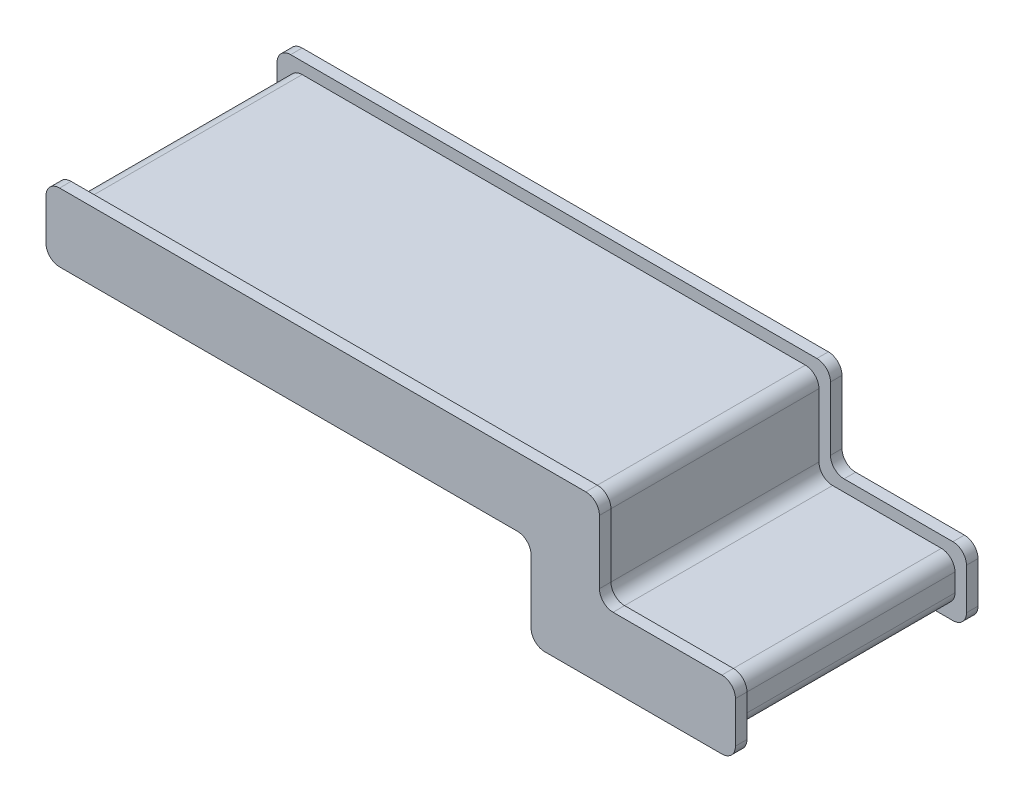
SolidWorks part; units mm, degrees
material "ABS"
ref_plane "X-Y Datum" through (0, 0, 0) normal (0, 0, 1) x (1, 0, 0)
ref_plane "X-Z Datum" through (0, 0, 0) normal (0, 1, 0) x (1, 0, 0)
ref_plane "Y-Z Datum" through (0, 0, 0) normal (1, 0, 0) x (0, 0, -1)
sketch "Sketch2" plane through (0, 0, 0) normal (0, 0, 1) x (1, 0, 0)
  line L6 (107, 10) -> (0, 10)
  line L7 (107, 10) -> (107, 0)
  line L8 (107, 0) -> (0, 0)
  line L9 (0, 10) -> (0, 0)
  dimension "D1" = 107
  dimension "D2" = 10
extrude "Boss-Extrude1" add sketch "Sketch2" along normal blind 48.42
sketch "Sketch3" plane through (0, 0, 48.42) normal (0, 0, 1) x (1, 0, 0)
  line L1 (107, 10) -> (117, 10)
  line L2 (107, 10) -> (107, -20)
  line L3 (107, -20) -> (117, -20)
  line L4 (117, 10) -> (117, -10)
  line L5 (117, -20) -> (147, -20)
  line L7 (117, -10) -> (147, -10)
  line L8 (147, -20) -> (147, -10)
  dimension "D1" = 10
  dimension "D2" = 30
  dimension "D3" = 10
  dimension "D4" = 30
extrude "Boss-Extrude2" add sketch "Sketch3" against normal up to surface (48.42 mm away) up to face at (53.5, 5, 0)
sketch "Sketch4" plane through (0, 0, 48.42) normal (0, 0, 1) x (1, 0, 0)
  line L0 (0, 10) -> (0, 0) construction
  line L1 (-2.54, 12.54) -> (119.54, 12.54)
  line L2 (-2.54, 12.54) -> (-2.54, -2.54)
  line L3 (-2.54, -2.54) -> (104.46, -2.54)
  line L12 (149.54, -22.54) -> (149.54, -7.46)
  line L13 (117, 10) -> (0, 10) construction
  line L14 (0, 0) -> (107, 0) construction
  line L15 (119.54, -7.46) -> (149.54, -7.46)
  line L16 (107, -20) -> (147, -20) construction
  line L17 (117, -10) -> (117, 10) construction
  line L18 (147, -10) -> (117, -10) construction
  line L19 (147, -20) -> (147, -10) construction
  line L20 (104.46, -22.54) -> (149.54, -22.54)
  line L21 (104.46, -2.54) -> (104.46, -22.54)
  line L22 (119.54, 12.54) -> (119.54, -7.46)
  line L23 (107, 0) -> (107, -20) construction
  point P18 (117, 0)
  dimension "D1" = 2.54
  dimension "D2" = 2.54
  dimension "D3" = 2.54
  dimension "D4" = 2.54
  dimension "D5" = 2.54
  dimension "D6" = 2.54
  dimension "D7" = 2.54
  dimension "D8" = 2.54
extrude "Boss-Extrude3" add sketch "Sketch4" along normal blind 2.54
sketch "Sketch5" plane through (0, 0, 0) normal (0, 0, -1) x (-1, 0, 0)
  line L0 (-119.54, 12.54) -> (-119.54, -7.46)
  line L1 (-149.54, -7.46) -> (-119.54, -7.46)
  line L2 (-149.54, -7.46) -> (-149.54, -22.54)
  line L11 (-104.46, -2.54) -> (2.54, -2.54)
  line L12 (2.54, 12.54) -> (2.54, -2.54)
  line L13 (-149.54, -22.54) -> (-104.46, -22.54)
  line L14 (-104.46, -2.54) -> (-104.46, -22.54)
  line L15 (-119.54, 12.54) -> (2.54, 12.54)
extrude "Boss-Extrude4" add sketch "Sketch5" along normal blind 2.54
fillet "Fillet1" radius 3 23 edges at (104.46, -22.54, -1.27) (107, -20, 24.21) (107, 0, 24.21) (104.46, -2.54, -1.27) (104.46, -22.54, 49.69) (104.46, -2.54, 49.69) (-2.54, -2.54, -1.27) (-2.54, -2.54, 49.69) (-2.54, 12.54, 49.69) (0, 10, 24.21) (-2.54, 12.54, -1.27) (119.54, 12.54, -1.27) (119.54, -7.46, -1.27) (149.54, -22.54, -1.27) (149.54, -7.46, -1.27) (117, 10, 24.21) (119.54, 12.54, 49.69) (119.54, -7.46, 49.69) (117, -10, 24.21) (147, -20, 24.21) (147, -10, 24.21) (149.54, -22.54, 49.69) (149.54, -7.46, 49.69)
